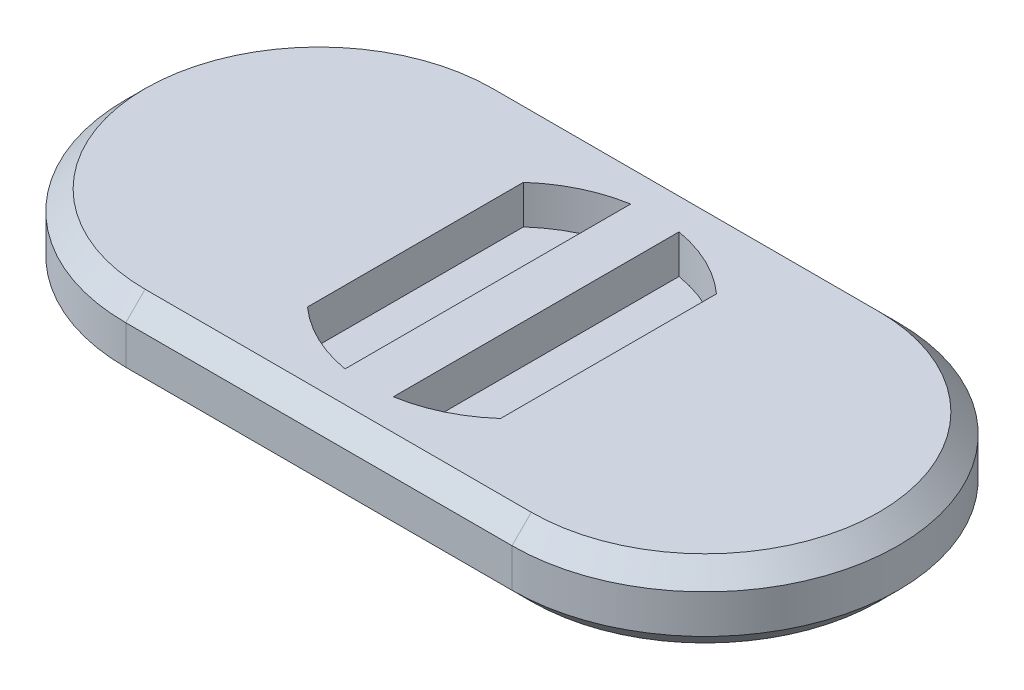
SolidWorks part; units mm, degrees
ref_plane "Front Plane" through (0, 0, 0) normal (0, 0, 1) x (1, 0, 0)
ref_plane "Top Plane" through (0, 0, 0) normal (0, 1, 0) x (1, 0, 0)
ref_plane "Right Plane" through (0, 0, 0) normal (1, 0, 0) x (0, 0, -1)
sketch "Sketch1" plane through (0, 0, 0) normal (0, 1, 0) x (1, 0, 0)
  line L0 (-20, 0) -> (20, 0) construction
  line L1 (-20, 20) -> (20, 20)
  line L2 (-20, -20) -> (20, -20)
  arc A0 (-20, 20) -> (-20, -20) centre (-20, 0) ccw
  arc A1 (20, -20) -> (20, 20) centre (20, 0) ccw
  point P2 (0, 0)
  dimension "D1" = 40
  dimension "D2" = 40
extrude "Boss-Extrude1" add sketch "Sketch1" along normal blind 8
sketch "Sketch2" plane through (0, 8, 0) normal (0, 1, 0) x (1, 0, 0)
  line L0 (-10, 11.1803) -> (10, 11.1803) construction
  line L2 (-10, -11.1803) -> (-10, 11.1803)
  line L4 (10, -11.1803) -> (10, 11.1803)
  line L5 (-10, -11.1803) -> (10, 11.1803) construction
  line L6 (-10, 11.1803) -> (10, -11.1803) construction
  line L9 (-2.5, 14.7902) -> (-2.5, -14.7902)
  line L11 (2.5, 14.7902) -> (2.5, -14.7902)
  arc A0 (-10, -11.1803) -> (-2.5, -14.7902) centre (0, 0) ccw
  arc A1 (10, 11.1803) -> (2.5, 14.7902) centre (0, 0) ccw
  arc A2 (-2.5, 14.7902) -> (-10, 11.1803) centre (0, 0) ccw
  arc A3 (2.5, -14.7902) -> (10, -11.1803) centre (0, 0) ccw
  point P3 (0, 0)
  point P15 (0, 0)
  dimension "D1" = 30
  dimension "D2" = 20
  dimension "D3" = 5
  dimension "D4" = 29.5804
extrude "Cut-Extrude5" cut sketch "Sketch2" against normal blind 4
chamfer "Chamfer1" distance 2 angle 45 8 edges at (-40, 8, 0) (0, 8, 20) (0, 8, -20) (40, 8, 0) (-40, 0, 0) (0, 0, 20) (0, 0, -20) (40, 0, 0)
